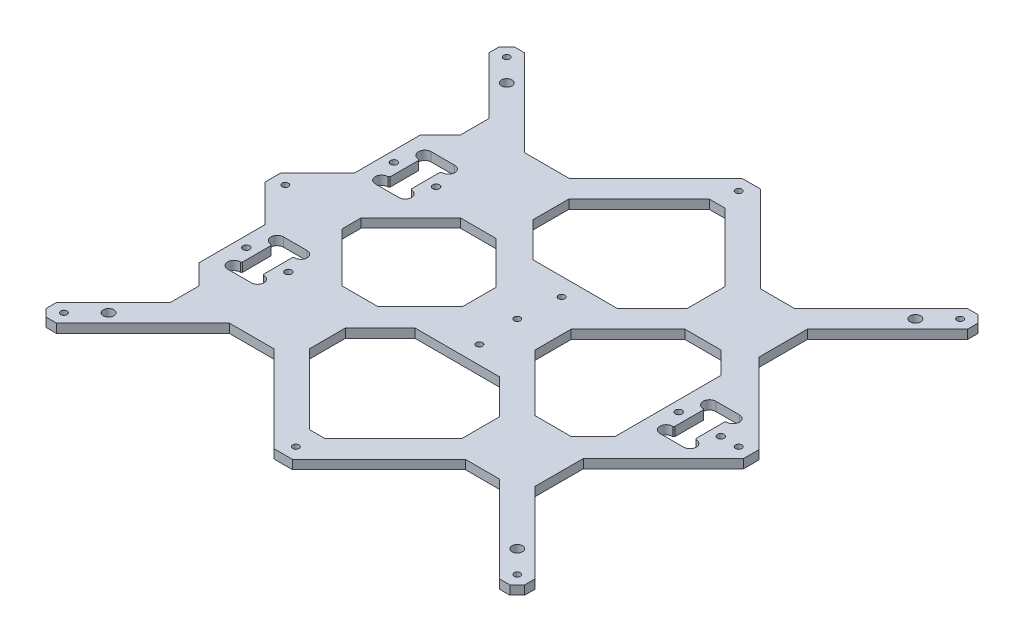
SolidWorks part; units mm, degrees
material "6063-O, Extruded Rod (SS)"
ref_plane "Front Plane" through (0, 0, 0) normal (0, 0, 1) x (1, 0, 0)
ref_plane "Top Plane" through (0, 0, 0) normal (0, 1, 0) x (1, 0, 0)
ref_plane "Right Plane" through (0, 0, 0) normal (1, 0, 0) x (0, 0, -1)
sketch "Sketch2" plane through (0, 0, 0) normal (0, 1, 0) x (1, 0, 0)
  line L0 (162, 177.023) -> (141.977, 157)
  line L1 (141.977, 157) -> (125, 157)
  line L2 (125, 157) -> (101.5, 180.5)
  line L3 (101.5, 189.5) -> (125, 213)
  line L4 (125, 213) -> (141.977, 213)
  line L5 (141.977, 213) -> (162, 192.977)
  line L6 (251.5, 210.0147) -> (240.9853, 220.5294)
  line L7 (240.9853, 220.5294) -> (224.0147, 220.5294)
  line L8 (224.0147, 220.5294) -> (197, 193.5147)
  line L9 (197, 176.4853) -> (224.0147, 149.4706)
  line L10 (224.0147, 149.4706) -> (240.9853, 149.4706)
  line L11 (240.9853, 149.4706) -> (251.5, 159.9853)
  line L12 (184.4001, 296) -> (225.4001, 255)
  line L13 (225.4001, 255) -> (241.5147, 255)
  line L14 (241.5147, 255) -> (282.5147, 296)
  line L15 (282.5147, 296) -> (287.4852, 296)
  line L16 (287.4852, 296) -> (291, 292.4852)
  line L17 (291, 292.4852) -> (291, 287.5147)
  line L18 (291, 287.5147) -> (253, 249.5147)
  line L19 (253, 249.5147) -> (253, 226.667)
  line L20 (253, 226.667) -> (291, 188.667)
  line L21 (291, 188.667) -> (291, 181.333)
  line L22 (291, 181.333) -> (253, 143.333)
  line L23 (253, 143.333) -> (253, 120.4853)
  line L24 (253, 120.4853) -> (291, 82.4853)
  line L25 (291, 82.4853) -> (291, 77.5148)
  line L26 (291, 77.5148) -> (287.4852, 74)
  line L27 (287.4852, 74) -> (282.5147, 74)
  line L28 (282.5147, 74) -> (241.5147, 115)
  line L29 (241.5147, 115) -> (225.4001, 115)
  line L30 (225.4001, 115) -> (184.4001, 74)
  line L31 (184.4001, 74) -> (175.5999, 74)
  line L32 (175.5999, 74) -> (134.5999, 115)
  line L33 (134.5999, 115) -> (113.4853, 115)
  line L34 (113.4853, 115) -> (72.4853, 74)
  line L35 (72.4853, 74) -> (67.5148, 74)
  line L36 (67.5148, 74) -> (64, 77.5148)
  line L37 (64, 77.5148) -> (64, 82.4853)
  line L38 (64, 82.4853) -> (91, 109.4853)
  line L39 (91, 109.4853) -> (91, 123)
  line L40 (91, 123) -> (81.5, 132.5)
  line L41 (81.5, 132.5) -> (81.5, 163.7609)
  line L42 (81.5, 163.7609) -> (64, 181.2609)
  line L43 (64, 188.7391) -> (81.5, 206.2391)
  line L44 (81.5, 206.2391) -> (81.5, 237.5)
  line L45 (81.5, 237.5) -> (91, 247)
  line L46 (91, 247) -> (91, 260.5147)
  line L47 (91, 260.5147) -> (64, 287.5147)
  line L48 (64, 287.5147) -> (64, 292.4852)
  line L49 (64, 292.4852) -> (67.5148, 296)
  line L50 (67.5148, 296) -> (72.4853, 296)
  line L51 (72.4853, 296) -> (113.4853, 255)
  line L52 (113.4853, 255) -> (134.5999, 255)
  line L53 (134.5999, 255) -> (175.5999, 296)
  line L54 (175.5999, 296) -> (184.4001, 296)
  line L55 (143, 246.4158) -> (143, 229.5663)
  line L56 (143, 229.5663) -> (159.5663, 213)
  line L57 (159.5663, 213) -> (199.5147, 213)
  line L58 (199.5147, 213) -> (216, 229.4853)
  line L59 (216, 229.4853) -> (216, 247.4296)
  line L60 (216, 247.4296) -> (183.6826, 279.747)
  line L61 (183.6826, 279.747) -> (176.3174, 279.7332)
  line L62 (176.3174, 279.7332) -> (143, 246.4158)
  line L63 (143, 123.5842) -> (143, 140.4337)
  line L64 (143, 140.4337) -> (159.5663, 157)
  line L65 (159.5663, 157) -> (199.5147, 157)
  line L66 (199.5147, 157) -> (216, 140.5147)
  line L67 (216, 140.5147) -> (216, 122.5704)
  line L68 (216, 122.5704) -> (183.6826, 90.253)
  line L69 (183.6826, 90.253) -> (176.3174, 90.2668)
  line L70 (176.3174, 90.2668) -> (143, 123.5842)
  line L71 (101.5, 226.75) -> (101.5, 213.25)
  line L72 (271.5, 191.75) -> (271.5, 178.25)
  line L73 (101.5, 156.75) -> (101.5, 143.25)
  line L74 (91.5, 226.75) -> (91.5, 213.25)
  line L75 (261.5, 191.75) -> (261.5, 178.25)
  line L76 (91.5, 156.75) -> (91.5, 143.25)
  line L77 (93.6792, 358.4107) -> (93.6792, 347.8262)
  line L78 (93.6792, 347.8262) -> (93.9406, 345.7354)
  line L79 (93.9406, 345.7354) -> (94.4633, 344.2327)
  line L80 (94.4633, 344.2327) -> (95.182, 343.1873)
  line L81 (95.182, 343.1873) -> (96.1846, 341.9648)
  line L82 (96.1846, 341.9648) -> (97.8105, 341.4329)
  line L83 (97.8105, 341.4329) -> (99.6248, 341.0966)
  line L84 (99.6248, 341.0966) -> (101.977, 341.3579)
  line L85 (101.977, 341.3579) -> (104.0024, 342.4033)
  line L86 (104.0024, 342.4033) -> (105.1131, 344.2327)
  line L87 (105.1131, 344.2327) -> (105.5705, 346.7155)
  line L88 (105.5705, 346.7155) -> (105.5705, 349.1983)
  line L89 (105.5705, 349.1983) -> (105.5705, 358.4107)
  line L90 (79.8932, 349.3289) -> (80.0892, 349.3289)
  line L91 (80.0892, 349.3289) -> (81.0039, 348.8063)
  line L92 (81.0039, 348.8063) -> (82.0493, 347.4342)
  line L93 (82.0493, 347.4342) -> (86.4922, 341.0966)
  line L94 (73.5556, 341.1619) -> (73.5556, 358.4107)
  line L95 (73.5556, 358.4107) -> (80.6119, 358.4107)
  line L96 (80.6119, 358.4107) -> (82.768, 357.7574)
  line L97 (82.768, 357.7574) -> (83.8134, 356.7773)
  line L98 (83.8134, 356.7773) -> (84.5321, 355.4706)
  line L99 (84.5321, 355.4706) -> (84.8588, 353.7065)
  line L100 (84.8588, 353.7065) -> (84.5321, 352.0078)
  line L101 (84.5321, 352.0078) -> (83.6827, 350.5703)
  line L102 (83.6827, 350.5703) -> (82.5067, 349.8517)
  line L103 (82.5067, 349.8517) -> (81.3306, 349.525)
  line L104 (81.3306, 349.525) -> (79.8932, 349.3289)
  line L105 (79.8932, 349.3289) -> (78.1291, 349.3289)
  line L106 (78.1291, 349.3289) -> (73.5556, 349.3289)
  line L107 (113.0897, 345.4442) -> (114.2004, 343.4842)
  line L108 (114.2004, 343.4842) -> (116.6178, 341.8507)
  line L109 (116.6178, 341.8507) -> (118.9699, 341.1974)
  line L110 (118.9699, 341.1974) -> (122.4328, 341.7201)
  line L111 (122.4328, 341.7201) -> (124.0662, 343.0268)
  line L112 (124.0662, 343.0268) -> (125.2422, 345.1176)
  line L113 (125.2422, 345.1176) -> (125.2422, 346.359)
  line L114 (125.2422, 346.359) -> (124.9156, 347.4697)
  line L115 (124.9156, 347.4697) -> (123.7395, 348.7764)
  line L116 (123.7395, 348.7764) -> (122.5635, 349.2991)
  line L117 (122.5635, 349.2991) -> (116.7485, 351.0632)
  line L118 (116.7485, 351.0632) -> (115.0497, 352.1739)
  line L119 (115.0497, 352.1739) -> (114.0044, 353.4153)
  line L120 (114.0044, 353.4153) -> (113.8737, 354.5914)
  line L121 (113.8737, 354.5914) -> (114.135, 356.3554)
  line L122 (114.135, 356.3554) -> (115.3764, 357.6622)
  line L123 (115.3764, 357.6622) -> (117.4672, 358.4462)
  line L124 (117.4672, 358.4462) -> (120.0807, 358.5769)
  line L125 (120.0807, 358.5769) -> (122.8248, 357.8582)
  line L126 (122.8248, 357.8582) -> (123.9355, 356.8128)
  line L127 (123.9355, 356.8128) -> (124.3929, 355.5714)
  line L128 (130.9954, 341.0312) -> (137.9864, 358.5414)
  line L129 (137.9864, 358.5414) -> (139.0972, 358.5414)
  line L130 (139.0972, 358.5414) -> (145.9575, 341.0312)
  line L131 (143.9343, 346.1951) -> (133.0803, 346.1927)
  line L132 (55, 341.1619) -> (55, 358.4107)
  line L133 (55, 358.4107) -> (62.0563, 358.4107)
  line L134 (62.0563, 358.4107) -> (64.2125, 357.7574)
  line L135 (64.2125, 357.7574) -> (65.2578, 356.7773)
  line L136 (65.2578, 356.7773) -> (65.9765, 355.4706)
  line L137 (65.9765, 355.4706) -> (66.3032, 353.7065)
  line L138 (66.3032, 353.7065) -> (65.9765, 352.0078)
  line L139 (65.9765, 352.0078) -> (65.1272, 350.5703)
  line L140 (65.1272, 350.5703) -> (63.9511, 349.8517)
  line L141 (63.9511, 349.8517) -> (62.7751, 349.525)
  line L142 (62.7751, 349.525) -> (61.3376, 349.3289)
  line L143 (61.3376, 349.3289) -> (59.5735, 349.3289)
  line L144 (59.5735, 349.3289) -> (55, 349.3289)
  line L145 (251.5, 210.0147) -> (251.5, 159.9853)
  line L146 (197, 193.5147) -> (197, 176.4853)
  line L147 (64, 188.7391) -> (64, 181.2609)
  line L148 (101.5, 189.5) -> (101.5, 180.5)
  line L149 (162, 192.977) -> (162, 177.023)
  line L150 (102.1, 142.75) -> (102, 142.75)
  line L151 (272.1, 177.75) -> (272, 177.75)
  line L152 (102.1, 212.75) -> (102, 212.75)
  line L153 (90.9, 142.75) -> (91, 142.75)
  line L154 (260.9, 177.75) -> (261, 177.75)
  line L155 (90.9, 212.75) -> (91, 212.75)
  line L156 (102, 142.75) -> (101.5, 143.25)
  line L157 (272, 177.75) -> (271.5, 178.25)
  line L158 (102, 212.75) -> (101.5, 213.25)
  line L159 (91, 142.75) -> (91.5, 143.25)
  line L160 (261, 177.75) -> (261.5, 178.25)
  line L161 (91, 212.75) -> (91.5, 213.25)
  line L162 (102.1, 157.25) -> (102, 157.25)
  line L163 (272.1, 192.25) -> (272, 192.25)
  line L164 (102.1, 227.25) -> (102, 227.25)
  line L165 (90.9, 157.25) -> (91, 157.25)
  line L166 (260.9, 192.25) -> (261, 192.25)
  line L167 (90.9, 227.25) -> (91, 227.25)
  line L168 (101.5, 156.75) -> (102, 157.25)
  line L169 (271.5, 191.75) -> (272, 192.25)
  line L170 (101.5, 226.75) -> (102, 227.25)
  line L171 (91.5, 156.75) -> (91, 157.25)
  line L172 (261.5, 191.75) -> (261, 192.25)
  line L173 (91.5, 226.75) -> (91, 227.25)
  line L174 (90.9, 163.25) -> (102.1, 163.25)
  line L175 (260.9, 198.25) -> (272.1, 198.25)
  line L176 (90.9, 233.25) -> (102.1, 233.25)
  line L177 (90.9, 136.75) -> (102.1, 136.75)
  line L178 (260.9, 171.75) -> (272.1, 171.75)
  line L179 (90.9, 206.75) -> (102.1, 206.75)
  arc A0 (102.1, 206.75) -> (102.1, 212.75) centre (102.1, 209.75) ccw
  arc A1 (272.1, 171.75) -> (272.1, 177.75) centre (272.1, 174.75) ccw
  arc A2 (102.1, 136.75) -> (102.1, 142.75) centre (102.1, 139.75) ccw
  arc A3 (90.9, 142.75) -> (90.9, 136.75) centre (90.9, 139.75) ccw
  arc A4 (90.9, 212.75) -> (90.9, 206.75) centre (90.9, 209.75) ccw
  arc A5 (260.9, 177.75) -> (260.9, 171.75) centre (260.9, 174.75) ccw
  arc A6 (102.1, 157.25) -> (102.1, 163.25) centre (102.1, 160.25) ccw
  arc A7 (102.1, 227.25) -> (102.1, 233.25) centre (102.1, 230.25) ccw
  arc A8 (272.1, 192.25) -> (272.1, 198.25) centre (272.1, 195.25) ccw
  arc A9 (90.9, 163.25) -> (90.9, 157.25) centre (90.9, 160.25) ccw
  arc A10 (260.9, 198.25) -> (260.9, 192.25) centre (260.9, 195.25) ccw
  arc A11 (90.9, 233.25) -> (90.9, 227.25) centre (90.9, 230.25) ccw
  circle A12 centre (318.6, 4.9) radius 2.55
  circle A13 centre (318.6, 28.1) radius 2.55
  circle A14 centre (295.4, 28.1) radius 2.55
  circle A15 centre (295.4, 4.9) radius 2.55
  circle A16 centre (281.6, 4.9) radius 2.55
  circle A17 centre (258.4, 4.9) radius 2.55
  circle A18 centre (258.4, 28.1) radius 2.55
  circle A19 centre (281.6, 28.1) radius 2.55
  circle A20 centre (111.6, 4.9) radius 2.55
  circle A21 centre (111.6, 28.1) radius 2.55
  circle A22 centre (88.4, 28.1) radius 2.55
  circle A23 centre (88.4, 4.9) radius 2.55
  circle A24 centre (74.6, 4.9) radius 2.55
  circle A25 centre (74.6, 28.1) radius 2.55
  circle A26 centre (51.4, 28.1) radius 2.55
  circle A27 centre (51.4, 4.9) radius 2.55
  circle A28 centre (360, 39.8) radius 1.5
  circle A29 centre (10, 39.8) radius 1.5
  circle A30 centre (340, 359.8) radius 1.5
  circle A31 centre (30, 39.8) radius 1.5
  circle A32 centre (42.9, 67.8) radius 1.5
  circle A33 centre (340, 39.8) radius 1.5
  circle A34 centre (10, 359.8) radius 1.5
  circle A35 centre (350, 19.8) radius 1.5
  circle A36 centre (47, 99.8) radius 1.5
  circle A37 centre (3.7, 181.1) radius 1.5
  circle A38 centre (20, 19.8) radius 1.5
  circle A39 centre (4.9, 67.8) radius 1.5
  circle A40 centre (360, 359.8) radius 1.5
  circle A41 centre (42.9, 161.8) radius 1.5
  circle A42 centre (3.7, 99.8) radius 1.5
  circle A43 centre (30, 359.8) radius 1.5
  circle A44 centre (47, 174.7) radius 1.5
  circle A45 centre (4.9, 161.8) radius 1.5
  circle A46 centre (46.5, 269.3) radius 1.5
  circle A47 centre (15, 247.8) radius 1.5
  circle A48 centre (3.5, 269.3) radius 1.5
  circle A49 centre (15, 290.8) radius 1.5
  circle A50 centre (180, 80) radius 1.5
  circle A51 centre (180, 290) radius 1.5
  circle A52 centre (285, 80) radius 1.5
  circle A53 centre (70, 290) radius 1.5
  circle A54 centre (285, 290) radius 1.5
  circle A55 centre (70, 185) radius 1.5
  circle A56 centre (180, 185) radius 1.5
  circle A57 centre (285, 185) radius 1.5
  circle A58 centre (256.5, 185) radius 1.6
  circle A59 centre (276.5, 185) radius 1.6
  circle A60 centre (106.5, 220) radius 1.6
  circle A61 centre (106.5, 150) radius 1.6
  circle A62 centre (86.5, 220) radius 1.6
  circle A63 centre (86.5, 150) radius 1.6
  circle A64 centre (70, 80) radius 1.5
  circle A65 centre (181.5, 165.5) radius 1.5
  circle A66 centre (181.5, 204.5) radius 1.5
  circle A67 centre (40, 7) radius 1.6
  circle A68 centre (331, 7) radius 1.6
  circle A69 centre (343, 7) radius 1.6
  circle A70 centre (120, 13) radius 1.6
  circle A71 centre (120, 4) radius 1.6
  circle A72 centre (230, 13) radius 1.6
  circle A73 centre (230, 4) radius 1.6
  circle A74 centre (333.4, 205) radius 2.1
  circle A75 centre (333.4, 88) radius 2.1
  circle A76 centre (26, 7) radius 1.6
  circle A77 centre (153, 13) radius 1.6
  circle A78 centre (153, 4) radius 1.6
  spline S0 degree 2 poles (5, 370) (2.5, 367.5) (0, 365) knots 1472.868668 1472.868668 1472.868668 1479.939736 1479.939736 1479.939736
  spline S1 degree 2 poles (365, 370) (185, 370) (5, 370) knots 1112.868668 1112.868668 1112.868668 1472.868668 1472.868668 1472.868668
  spline S2 degree 2 poles (370, 365) (367.5, 367.5) (365, 370) knots 1105.7976 1105.7976 1105.7976 1112.868668 1112.868668 1112.868668
  spline S3 degree 2 poles (370, 5) (370, 185) (370, 365) knots 745.7976 745.7976 745.7976 1105.7976 1105.7976 1105.7976
  spline S4 degree 2 poles (365, 0) (367.5, 2.5) (370, 5) knots 738.726533 738.726533 738.726533 745.7976 745.7976 745.7976
  spline S5 degree 2 poles (345, 0) (355, 0) (365, 0) knots 718.726533 718.726533 718.726533 738.726533 738.726533 738.726533
  spline S6 degree 2 poles (341, 4) (343, 2) (345, 0) knots 710.241251 710.241251 710.241251 718.726533 718.726533 718.726533
  spline S7 degree 2 poles (333, 4) (337, 4) (341, 4) knots 704.241251 704.241251 704.241251 710.241251 710.241251 710.241251
  spline S8 degree 2 poles (329, 0) (331, 2) (333, 4) knots 698.584397 698.584397 698.584397 704.241251 704.241251 704.241251
  spline S9 degree 2 poles (151, 0) (240, 0) (329, 0) knots 507.584397 507.584397 507.584397 698.584397 698.584397 698.584397
  spline S10 degree 2 poles (146, 5) (148.5, 2.5) (151, 0) knots 501.927543 501.927543 501.927543 507.584397 507.584397 507.584397
  spline S11 degree 2 poles (127, 5) (136.5, 5) (146, 5) knots 487.927543 487.927543 487.927543 501.927543 501.927543 501.927543
  spline S12 degree 2 poles (122, 0) (124.5, 2.5) (127, 5) knots 482.270688 482.270688 482.270688 487.927543 487.927543 487.927543
  spline S13 degree 2 poles (41, 0) (81.5, 0) (122, 0) knots 407.270688 407.270688 407.270688 482.270688 482.270688 482.270688
  spline S14 degree 2 poles (37, 4) (39, 2) (41, 0) knots 401.613834 401.613834 401.613834 407.270688 407.270688 407.270688
  spline S15 degree 2 poles (29, 4) (33, 4) (37, 4) knots 395.613834 395.613834 395.613834 401.613834 401.613834 401.613834
  spline S16 degree 2 poles (25, 0) (27, 2) (29, 4) knots 387.128553 387.128553 387.128553 395.613834 395.613834 395.613834
  spline S17 degree 2 poles (5, 0) (15, 0) (25, 0) knots 367.128553 367.128553 367.128553 387.128553 387.128553 387.128553
  spline S18 degree 2 poles (0, 5) (2.5, 2.5) (5, 0) knots 360.191742 360.191742 360.191742 367.128553 367.128553 367.128553
  spline S19 degree 2 poles (0, 365) (0, 185) (0, 5) knots 0 0 0 360.191742 360.191742 360.191742
  spline S20 degree 2 poles (93, 31.5) (100, 31.5) (107, 31.5) knots 1110.421356 1110.421356 1110.421356 1117.046356 1117.046356 1117.046356
  spline S21 degree 2 poles (88, 36.5) (90.5, 34) (93, 31.5) knots 1103.350288 1103.350288 1103.350288 1110.421356 1110.421356 1110.421356
  spline S22 degree 2 poles (83, 36.5) (85.5, 36.5) (88, 36.5) knots 1098.350288 1098.350288 1098.350288 1103.350288 1103.350288 1103.350288
  spline S23 degree 2 poles (73, 46.5) (78, 41.5) (83, 36.5) knots 1084.208153 1084.208153 1084.208153 1098.350288 1098.350288 1098.350288
  spline S24 degree 2 poles (55, 46.5) (64, 46.5) (73, 46.5) knots 1066.208153 1066.208153 1066.208153 1084.208153 1084.208153 1084.208153
  spline S25 degree 2 poles (50, 51.5) (52.5, 49) (55, 46.5) knots 1059.137085 1059.137085 1059.137085 1066.208153 1066.208153 1066.208153
  spline S26 degree 2 poles (50, 325) (50, 188.25) (50, 51.5) knots 787.637085 787.637085 787.637085 1059.137085 1059.137085 1059.137085
  spline S27 degree 2 poles (55, 330) (52.5, 327.5) (50, 325) knots 780.566017 780.566017 780.566017 787.637085 787.637085 787.637085
  spline S28 degree 2 poles (315, 330) (185, 330) (55, 330) knots 520.566017 520.566017 520.566017 780.566017 780.566017 780.566017
  spline S29 degree 2 poles (320, 325) (317.5, 327.5) (315, 330) knots 513.494949 513.494949 513.494949 520.566017 520.566017 520.566017
  spline S30 degree 2 poles (320, 51.5) (320, 188.25) (320, 325) knots 241.994949 241.994949 241.994949 513.494949 513.494949 513.494949
  spline S31 degree 2 poles (315, 46.5) (317.5, 49) (320, 51.5) knots 234.923882 234.923882 234.923882 241.994949 241.994949 241.994949
  spline S32 degree 2 poles (297, 46.5) (306, 46.5) (315, 46.5) knots 216.923882 216.923882 216.923882 234.923882 234.923882 234.923882
  spline S33 degree 2 poles (287, 36.5) (292, 41.5) (297, 46.5) knots 202.781746 202.781746 202.781746 216.923882 216.923882 216.923882
  spline S34 degree 2 poles (282, 36.5) (284.5, 36.5) (287, 36.5) knots 197.781746 197.781746 197.781746 202.781746 202.781746 202.781746
  spline S35 degree 2 poles (277, 31.5) (279.5, 34) (282, 36.5) knots 190.710678 190.710678 190.710678 197.781746 197.781746 197.781746
  spline S36 degree 2 poles (263, 31.5) (264, 31.5) (265, 31.5) (270, 31.5) (275, 31.5) (276, 31.5) (277, 31.5) knots 176.710678 176.710678 176.710678 178.710678 178.710678 188.710678 188.710678 190.710678 190.710678 190.710678
  spline S37 degree 2 poles (258, 36.5) (260.5, 34) (263, 31.5) knots 169.63961 169.63961 169.63961 176.710678 176.710678 176.710678
  spline S38 degree 2 poles (210, 36.5) (211.75, 36.5) (213.5, 36.5) (235.75, 36.5) (258, 36.5) knots 121.63961 121.63961 121.63961 125.13961 125.13961 169.63961 169.63961 169.63961
  spline S39 degree 2 poles (190, 16.5) (200, 26.5) (210, 36.5) knots 93.355339 93.355339 93.355339 121.63961 121.63961 121.63961
  spline S40 degree 2 poles (180, 16.5) (185, 16.5) (190, 16.5) knots 83.355339 83.355339 83.355339 93.355339 93.355339 93.355339
  spline S41 degree 2 poles (160, 36.5) (170, 26.5) (180, 16.5) knots 55.071068 55.071068 55.071068 83.355339 83.355339 83.355339
  spline S42 degree 2 poles (112, 36.5) (134.25, 36.5) (156.5, 36.5) (158.25, 36.5) (160, 36.5) knots 7.071068 7.071068 7.071068 51.571068 51.571068 55.071068 55.071068 55.071068
  spline S43 degree 2 poles (107, 31.5) (109.5, 34) (112, 36.5) knots 0 0 0 7.071068 7.071068 7.071068
extrude "Boss-Extrude2" add sketch "Sketch2" along normal blind 4.25 contours L43 L147 L42 L41 L40 L39 L38 L37 L36 L35 L34 L33 L32 L31 L30 L29 L28 L27 L26 L25 L24 L23 L22 L21 L20 L19 L18 L17 L16 L15 L14 L13 L12 L54 L53 L52 L51 L50 L49 L48 L47 L46 L45 L44 A66 A65 A64
sketch "Sketch3" plane through (0, 4.25, 0) normal (0, 1, 0) x (1, 0, 0)
  line L0 (181.5, 203) -> (181.5, 206) construction
  line L1 (180, 204.5) -> (183, 204.5) construction
  line L2 (180, 165.5) -> (183, 165.5) construction
  circle A0 centre (181.5, 204.5) radius 1.5 construction
  circle A1 centre (181.5, 204.5) radius 1.5 construction
  circle A2 centre (181.5, 165.5) radius 1.5 construction
ref_plane "Plane1" through (181.5, 0, 0) normal (1, 0, 0) x (0, 0, -1)
ref_plane "Plane2" through (0, 0, -165.5) normal (0, 0, 1) x (1, 0, 0)
ref_plane "Plane3" through (0, 0, -204.5) normal (0, 0, -1) x (-1, 0, 0)
sketch "Sketch4" plane through (0, 4.25, 0) normal (0, 1, 0) x (1, 0, 0)
  line L0 (70, 290) -> (80.6066, 279.3934) construction
  line L1 (91, 260.5147) -> (64, 287.5147) construction
  line L2 (285, 290) -> (274.3934, 279.3934) construction
  line L3 (291, 287.5147) -> (253, 249.5147) construction
  line L4 (285, 80) -> (274.3934, 90.6066) construction
  line L5 (253, 120.4853) -> (291, 82.4853) construction
  line L6 (70, 80) -> (80.6066, 90.6066) construction
  line L7 (113.4853, 115) -> (72.4853, 74) construction
  circle A0 centre (80.6066, 279.3934) radius 2.5
  circle A1 centre (274.3934, 279.3934) radius 2.5
  circle A2 centre (80.6066, 90.6066) radius 2.5
  circle A3 centre (274.3934, 90.6066) radius 2.5
  dimension "D1" = 5
  dimension "D4" = 5
  dimension "D7" = 5
  dimension "D8" = 5
  dimension "D2" = 15
  dimension "D3" = 15
  dimension "D5" = 15
  dimension "D6" = 15
extrude "Holes-to-drill" cut sketch "Sketch4" against normal through all
